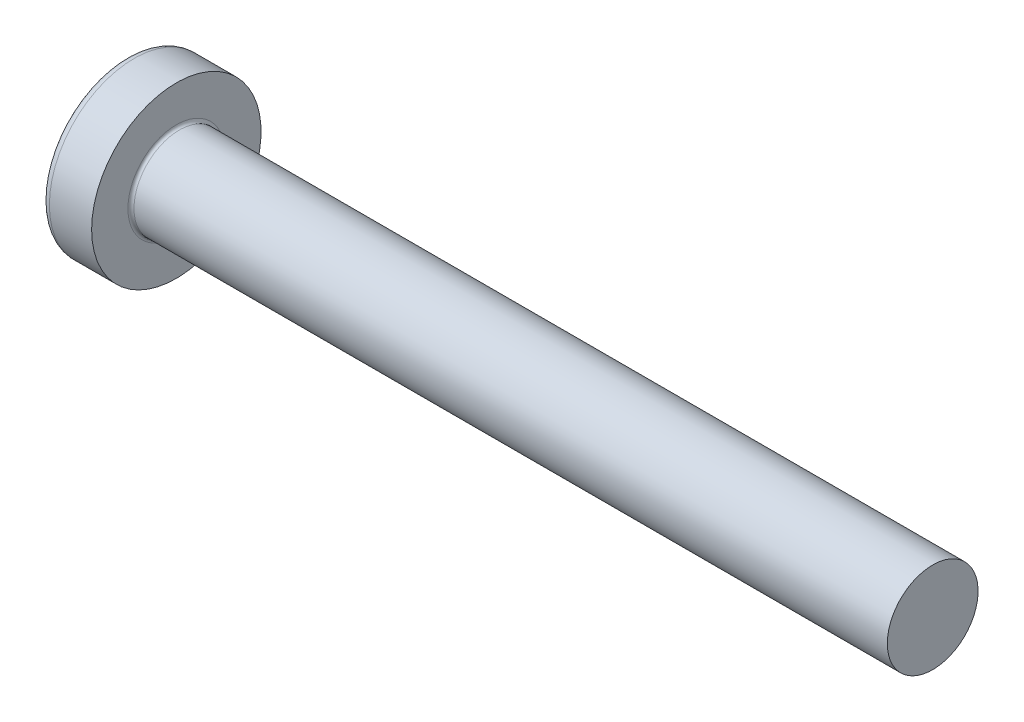
SolidWorks part; units mm, degrees
ref_plane "Plane1" through (0, 0, 0) normal (0, 0, 1) x (1, 0, 0)
ref_plane "Plane2" through (0, 0, 0) normal (0, 1, 0) x (1, 0, 0)
ref_plane "Plane3" through (0, 0, 0) normal (1, 0, 0) x (0, 0, -1)
sketch "BodySke" plane through (0, 0, 0) normal (0, 0, 1) x (1, 0, 0)
  line L0 (2.4, 1.5) -> (2.4, 2.8)
  line L1 (2.65, 6.35) -> (2.65, -3.175) construction
  line L2 (-25.4, 0) -> (127, 0) construction
  line L3 (27.4, 0) -> (0, 0)
  line L4 (2.4, 1.5) -> (27.4, 1.5)
  line L5 (27.4, 1.5) -> (27.4, 0)
  line L6 (1.0035, 2.8) -> (2.4, 2.8)
  line L8 (2.4, 6.35) -> (2.4, -3.175) construction
  arc A0 (0.7754, 2.6744) -> (0, 0) centre (5, 0) ccw
  arc A2 (0.7754, 2.6744) -> (1.0035, 2.8) centre (1.0035, 2.53) cw
revolve "Base-Revolve" add sketch "BodySke"
cosmetic thread "ThreadCosmetic"
fillet "Fillet1" radius 0.1 1 edges at (2.4, 0, 1.5)
sketch "Sketch3" plane through (0, 0, 0) normal (1, 0, 0) x (0, 0, -1)
  line L0 (0.37, -1.4) -> (-0.37, -1.4)
  line L1 (0.37, -1.4) -> (0.37, 1.4)
  line L2 (-0.37, 1.4) -> (0.37, 1.4)
  line L3 (-0.37, 1.4) -> (-0.37, -1.4)
ref_plane "Plane4" through (1.75, 0, 0) normal (1, 0, 0) x (0, 0, -1)
sketch "Sketch4" plane through (1.75, 0, 0) normal (1, 0, 0) x (0, 0, -1)
  line L0 (0.37, -0.5275) -> (-0.37, -0.5275)
  line L1 (0.37, -0.5275) -> (0.37, 0.5275)
  line L2 (-0.37, 0.5275) -> (0.37, 0.5275)
  line L3 (-0.37, 0.5275) -> (-0.37, -0.5275)
loft "Recess" cut profiles "Sketch3", "Sketch4"
pattern_circular "RecPat" count 2 every 90 about axis through (0, 0, 0) along (1, 0, 0) of "Recess"
sketch "RecCorSke" plane through (0, 0, 0) normal (0, 0, 1) x (1, 0, 0)
  line L0 (-3.175, 0) -> (15.875, 0) construction
  line L1 (-25.4, 0) -> (127, 0) construction
  line L2 (0, 0) -> (0, 0.6784)
  line L3 (0, 0.6784) -> (1.75, 0.556)
  line L4 (1.75, 0.556) -> (1.9307, 0)
  line L5 (1.9307, 0) -> (0, 0)
  dimension "Draft_angle" = 4
  dimension "Bottom_angle" = 18
revolve "RecessCore" cut sketch "RecCorSke" angle 360 about L0
sketch "ThdSchSke" plane through (0, 0, 0) normal (0, 0, 1) x (1, 0, 0)
  line L0 (3.4, -1.2195) -> (3.2036, -1.5)
  line L1 (3.4, -1.2195) -> (3.5964, -1.5)
  line L2 (3.5964, -1.5) -> (3.5964, -1.875)
  line L3 (-3.175, 0) -> (5.1513, 0) construction
  line L5 (3.5964, -1.875) -> (3.2036, -1.875)
  line L6 (3.2036, -1.875) -> (3.2036, -1.5)
  dimension "SideAngle" = 55
  dimension "VeeAngle" = 70
revolve "ThreadSchematic" [suppressed] cut sketch "ThdSchSke" angle 360 about L3
pattern_linear "ThdSchPat" [suppressed]
equation "\"D1@Sketch3\" = \"Cross_dia@Sketch3\" / 2"
equation "\"D2@Sketch3\" = \"Cross_width@Sketch3\" / 2"
equation "\"Depth@RecCorSke\" = \"Cross_depth@Plane4\""
equation "\"D1@Sketch4\" = \"Cross_width@Sketch3\""
equation "\"D2@Sketch4\" = \"Cross_dia@Sketch3\" - 2.0 * \"Cross_depth@Plane4\" * tan(26.5  * 0.017453292)"
equation "\"D3@Sketch4\" = \"D1@Sketch4\" / 2"
equation "\"D4@Sketch4\" = \"D2@Sketch4\" / 2"
equation "\"Thread_length@ThreadCosmetic\" = ((sgn( (\"Length@BodySke\" - \"Advance@BodySke\" * 2.0 ) - \"Thread_nom@BodySke\" )-1)*( (\"Length@BodySke\" - \"Advance@BodySke\" * 2.0 ) - \"Thread_nom@BodySke\" ))/-2+ \"Thread_nom@BodySke\""
equation "\"Thread_minor@ThdSchSke\" = \"Thread_minor@ThreadCosmetic\""
equation "\"Diameter@ThdSchSke\" = \"Diameter@BodySke\""
equation "\"Overcut@ThdSchSke\" = \"Diameter@BodySke\" * 1.25"
equation "\"Start@ThdSchSke\" = \"Head_ht@BodySke\" + \"Length@BodySke\" - \"Thread_length@ThreadCosmetic\"  '---Non-countersunk---"
equation "\"Num_threads@ThdSchPat\" = int( \"Thread_length@ThreadCosmetic\" / \"Advance@BodySke\" + 0.999 )  + 1"
equation "\"Advance@ThdSchPat\" = \"Thread_length@ThreadCosmetic\" /  (\"Num_threads@ThdSchPat\" - 1) 'relax it"
